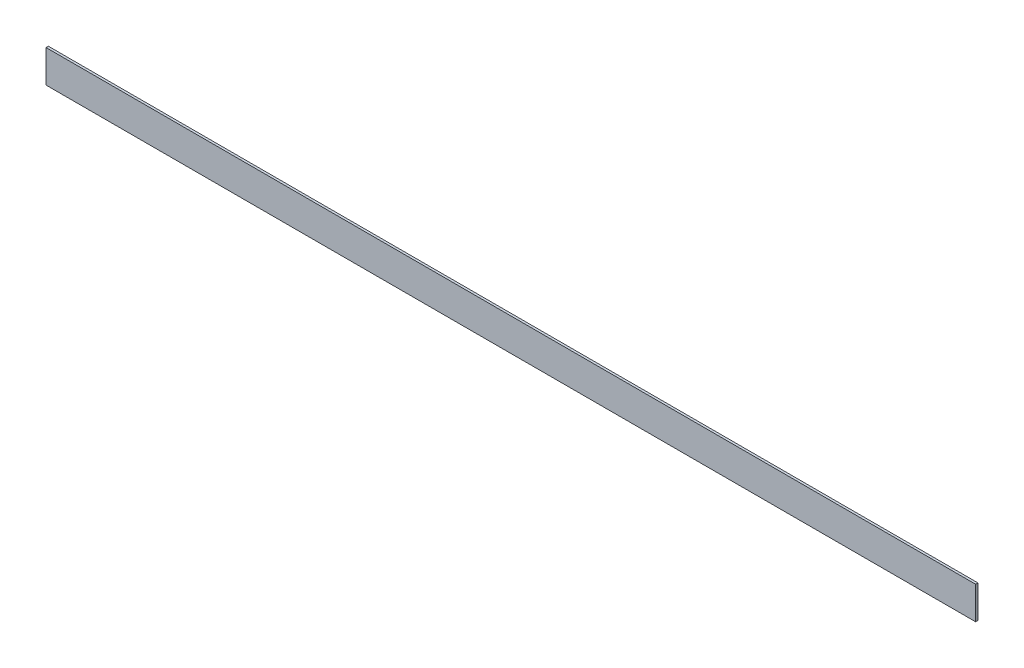
SolidWorks part; units mm, degrees
ref_plane "Front Plane" through (0, 0, 0) normal (0, 0, 1) x (1, 0, 0)
ref_plane "Top Plane" through (0, 0, 0) normal (0, 1, 0) x (1, 0, 0)
ref_plane "Right Plane" through (0, 0, 0) normal (1, 0, 0) x (0, 0, -1)
sketch "Sketch1" plane through (0, 0, 0) normal (0, 0, 1) x (1, 0, 0)
  line L1 (1000, -35) -> (-1000, -35)
  line L2 (1000, -35) -> (1000, 35)
  line L3 (1000, 35) -> (-1000, 35)
  line L4 (-1000, -35) -> (-1000, 35)
  line L5 (1000, -35) -> (-1000, 35) construction
  line L6 (1000, 35) -> (-1000, -35) construction
  point P0 (0, 0)
  dimension "D1" = 70
  dimension "D2" = 2000
extrude "Boss-Extrude1" add sketch "Sketch1" along normal blind 5
